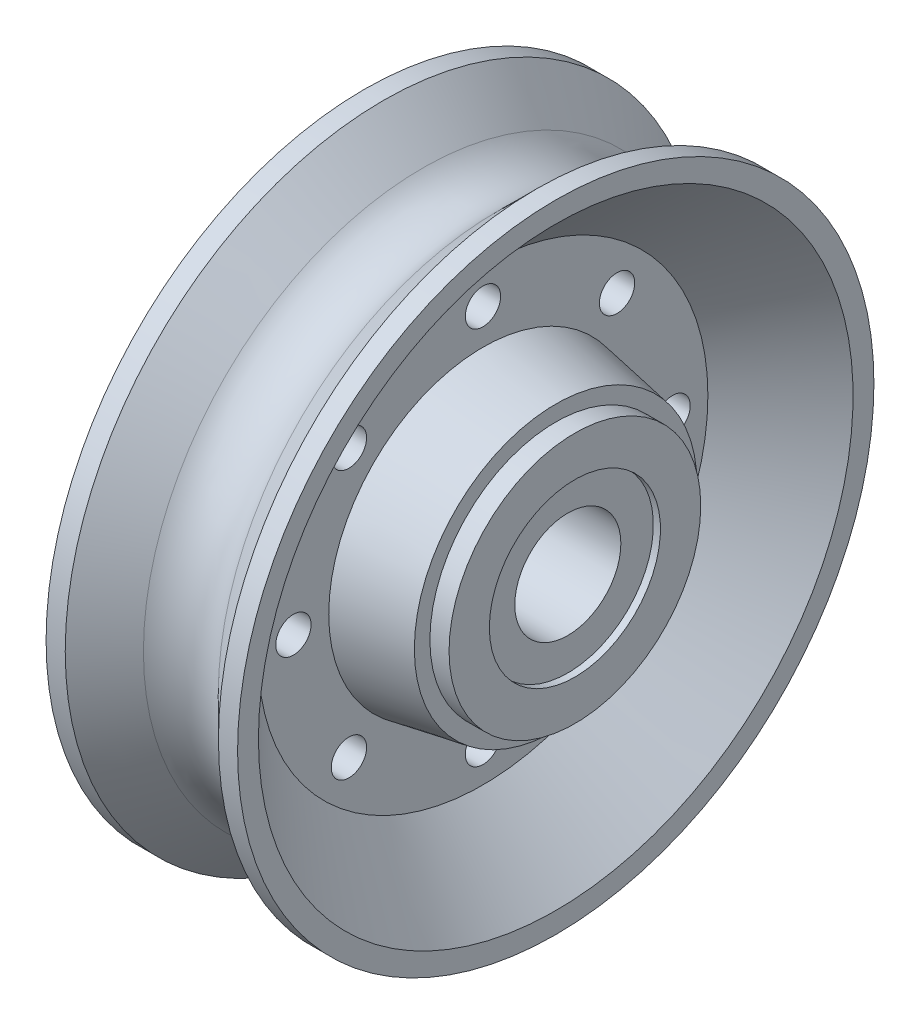
SolidWorks part; units mm, degrees
ref_plane "Front Plane" through (0, 0, 0) normal (0, 0, 1) x (1, 0, 0)
ref_plane "Top Plane" through (0, 0, 0) normal (0, 1, 0) x (1, 0, 0)
ref_plane "Right Plane" through (0, 0, 0) normal (1, 0, 0) x (0, 0, -1)
sketch "Sketch1" plane through (0, 0, 0) normal (0, 0, 1) x (1, 0, 0)
  line L0 (6.8792, 28.575) -> (8.599, 28.575)
  line L1 (-6.8792, 28.575) -> (-8.599, 28.575)
  line L2 (-6.8792, 28.575) -> (-3.3594, 25.0723)
  line L3 (10.3187, 12.7) -> (10.3188, 4.7625)
  line L4 (10.3188, 4.7625) -> (-10.3188, 4.7625)
  line L5 (-10.3188, 4.7625) -> (-10.3187, 12.7)
  line L6 (6.8792, 28.575) -> (3.3594, 25.0723)
  line L7 (-10.3187, 12.7) -> (-8.599, 12.7)
  line L8 (-10.3187, 0) -> (10.3187, 0) construction
  line L9 (-8.599, 12.7) -> (-8.599, 28.575)
  line L10 (8.599, 28.575) -> (8.599, 12.7)
  line L11 (8.599, 12.7) -> (10.3187, 12.7)
  arc A0 (-3.3594, 25.0723) -> (3.3594, 25.0723) centre (0, 28.448) ccw
  circle A1 centre (0, 28.448) radius 4.7625 construction
  circle A2 centre (0, -28.448) radius 4.7625 construction
  dimension "Rope Dia" = 9.525
  dimension "Width" = 20.6375
  dimension "Shaft Dia" = 9.525
  dimension "OD" = 57.15
  dimension "A" = 47.371
  dimension "D1" = 25.4
  dimension "D2" = 3.4396
  dimension "D3" = 1.7198
revolve "Revolve1" add sketch "Sketch1" angle 360 about L8
sketch "Sketch2" plane through (0, 0, 0) normal (0, 0, 1) x (1, 0, 0)
  line L0 (-10.3187, 12.7) -> (-8.599, 12.7)
  line L1 (-8.599, 12.7) -> (-2.0638, 13.8523)
  line L2 (-2.0638, 13.8523) -> (-2.0637, 20.1994)
  line L3 (-2.0637, 20.1994) -> (-10.3187, 28.4145)
  line L6 (-6.8792, 28.575) -> (-3.3594, 25.0723) construction
  line L7 (-10.3187, 12.7) -> (-10.3187, 28.4145)
  line L8 (0, 0) -> (0, 28.448) construction
  line L9 (10.3187, 12.7) -> (10.3187, 28.4145)
  line L10 (2.0637, 20.1994) -> (10.3187, 28.4145)
  line L11 (2.0638, 13.8523) -> (2.0637, 20.1994)
  line L12 (8.599, 12.7) -> (2.0638, 13.8523)
  line L13 (10.3187, 12.7) -> (8.599, 12.7)
  dimension "D1" = 2.54
  dimension "D2" = 4.1275
  dimension "D4" = 6.3471
  dimension "D3" = 10
revolve "Cut-Revolve1" cut sketch "Sketch2" angle 360 about L8
sketch "Sketch3" plane through (0, 0, 0) normal (1, 0, 0) x (0, 0, -1)
  line L0 (0, 20.1994) -> (0, 13.8523) construction
  circle A0 centre (0, 17.0259) radius 1.5868
  dimension "D2" = 3.1735
  dimension "D1" = 6.3471
extrude "Cut-Extrude1" cut sketch "Sketch3" against normal through all and the other way through all
pattern_circular "CirPattern1" count 8 over 360 about axis through (0, 0, 0) along (1, 0, 0) of "Cut-Extrude1"
sketch "Sketch4" plane through (-10.3188, 0, 0) normal (-1, 0, 0) x (0, 0, 1)
  circle A2 centre (0, 0) radius 11.303
  circle A3 centre (0, 0) radius 11.303
  circle A5 centre (0, 0) radius 14.605
  circle A6 centre (0, 0) radius 14.605
  dimension "D1" = 1.397
  dimension "D2" = 1.905
extrude "Cut-Extrude2" cut sketch "Sketch4" against normal blind 1.7198
sketch "Sketch5" plane through (-10.3188, 0, 0) normal (-1, 0, 0) x (0, 0, 1)
  circle A2 centre (0, 0) radius 7.6835
  circle A3 centre (0, 0) radius 7.6835
  dimension "D1" = 2.921
extrude "Cut-Extrude3" cut sketch "Sketch5" against normal blind 0.635
mirror "Mirror1" about plane through (0, 0, 0) normal (1, 0, 0) of "Cut-Extrude3", "Cut-Extrude2"
equation "\"D1@Sketch1\" = \"OD@Sketch1\"/2.250"
equation "\"D2@Sketch1\" = \"Width@Sketch1\"/6"
equation "\"D3@Sketch1\" = \"D2@Sketch1\"/2"
equation "\"D2@Sketch2\" = \"Width@Sketch1\"/5"
equation "\"D1@Sketch3\" = \"D4@Sketch2\""
equation "\"D2@Sketch3\" = \"D1@Sketch3\"*.5"
equation "\"D1@Cut-Extrude2\" = \"D3@Sketch1\""
